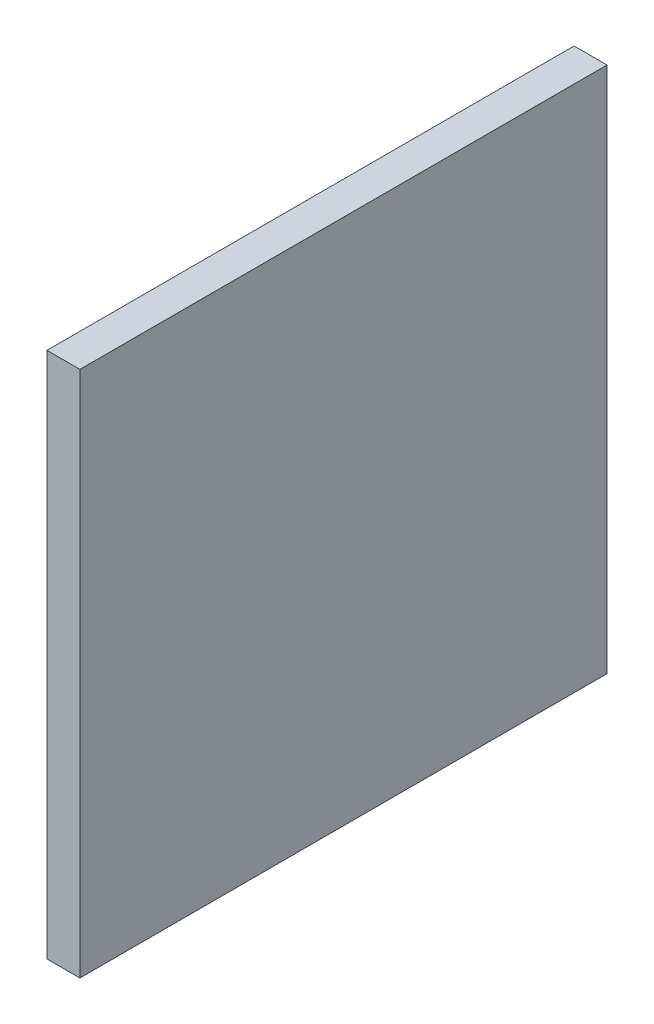
SolidWorks part; units mm, degrees
ref_plane "Front Plane" through (0, 0, 0) normal (0, 0, 1) x (1, 0, 0)
ref_plane "Top Plane" through (0, 0, 0) normal (0, 1, 0) x (1, 0, 0)
ref_plane "Right Plane" through (0, 0, 0) normal (1, 0, 0) x (0, 0, -1)
sketch "Sketch1" plane through (0, 0, 0) normal (1, 0, 0) x (0, 0, -1)
  line L1 (0, 0) -> (-80, 0)
  line L2 (0, 0) -> (0, 80)
  line L3 (0, 80) -> (-80, 80)
  line L4 (-80, 0) -> (-80, 80)
  dimension "D1" = 80
  dimension "D2" = 80
extrude "Boss-Extrude1" add sketch "Sketch1" along normal blind 5
